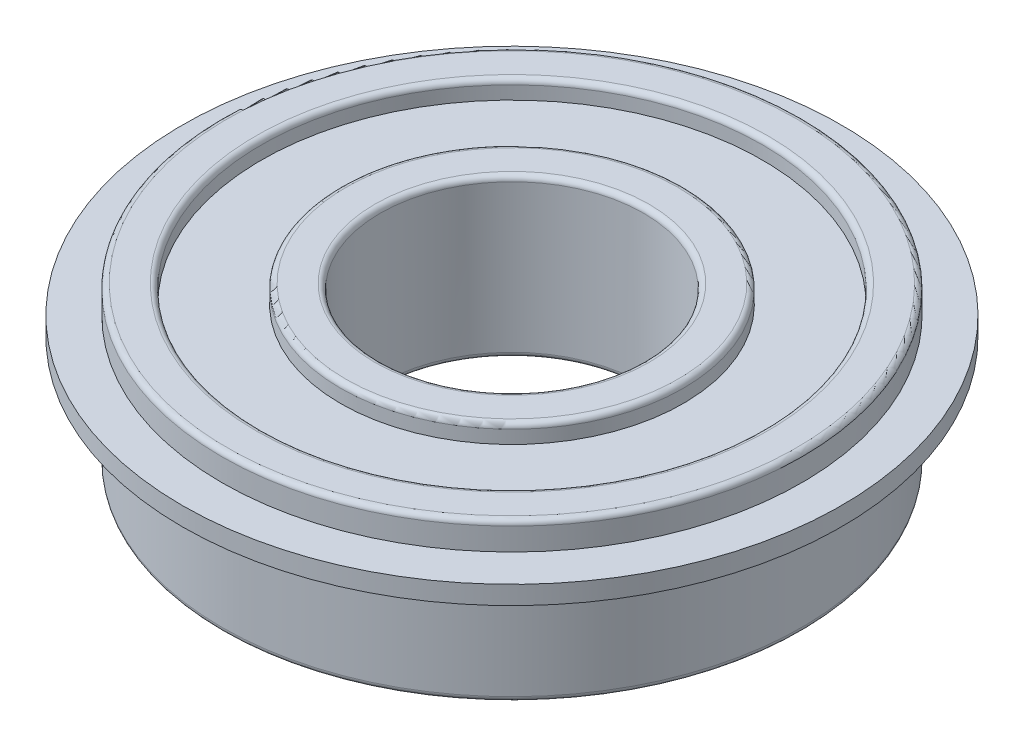
SolidWorks part; units mm, degrees
ref_plane "前视基准面" through (0, 0, 0) normal (0, 0, 1) x (1, 0, 0)
ref_plane "上视基准面" through (0, 0, 0) normal (0, 1, 0) x (1, 0, 0)
ref_plane "右视基准面" through (0, 0, 0) normal (1, 0, 0) x (0, 0, -1)
other "Configuration Table"
sketch "草图1" plane through (0, 0, 0) normal (0, 0, 1) x (1, 0, 0)
  line L0 (0, 4.6113) -> (0, -3.0029) construction
  line L1 (5, 6) -> (5, 0)
  line L2 (5, 0) -> (6.5, 0)
  line L3 (6.5, 0) -> (6.5, 0.7)
  line L4 (6.5, 0.7) -> (9.5, 0.7)
  line L5 (9.5, 0.7) -> (9.5, 0)
  line L6 (9.5, 0) -> (11, 0)
  line L7 (11, 0) -> (11, 6)
  line L8 (11, 6) -> (9.5, 6)
  line L9 (9.5, 6) -> (9.5, 5.3)
  line L10 (9.5, 5.3) -> (6.5, 5.3)
  line L11 (6.5, 5.3) -> (6.5, 6)
  line L12 (6.5, 6) -> (5, 6)
  dimension "D1" = 5
  dimension "D2" = 11
  dimension "D3" = 6
  dimension "D4" = 1.5
  dimension "D5" = 1.5
  dimension "D6" = 0.7
  dimension "D7" = 0.7
revolve "旋转1" add sketch "草图1" angle 360 about L0
fillet "圆角1" radius 0.2 8 edges at (0, 0, 5) (0, 0, 6.5) (0, 0, 9.5) (0, 0, 11) (0, 6, 6.5) (0, 6, 5) (0, 6, 11) (0, 6, 9.5)
sketch "草图2" plane through (0, 6, 0) normal (0, 1, 0) x (1, 0, 0)
  circle A0 centre (0, 0) radius 12.5
  circle A1 centre (0, 0) radius 11 construction
  circle A2 centre (0, 0) radius 11
  dimension "D1" = 25
extrude "凸台-拉伸1" add sketch "草图2" against normal blind 0.7 from offset 1.05 offset against normal yes
